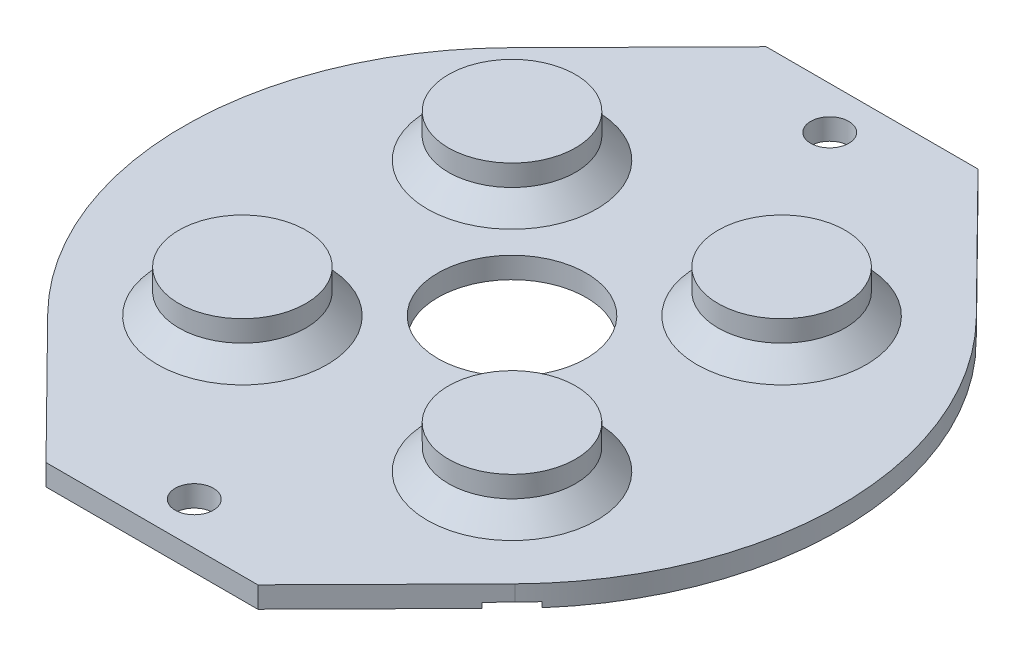
SolidWorks part; units mm, degrees
material "Silicon"
ref_plane "Front Plane" through (0, 0, 0) normal (0, 0, 1) x (1, 0, 0)
ref_plane "Top Plane" through (0, 0, 0) normal (0, 1, 0) x (1, 0, 0)
ref_plane "Right Plane" through (0, 0, 0) normal (1, 0, 0) x (0, 0, -1)
sketch "Sketch1" plane through (0, 0, 0) normal (0, 1, 0) x (1, 0, 0)
  line L0 (5, 17) -> (11.0323, 10.8876)
  line L1 (-5, -17) -> (5, -17)
  line L3 (-5, 17) -> (5, 17)
  line L7 (-5, 17) -> (-11.0323, 10.8876)
  line L8 (5, -17) -> (11.0323, -10.8876)
  line L9 (-5, -17) -> (-11.0323, -10.8876)
  arc A0 (-11.0323, 10.8876) -> (-11.0323, -10.8876) centre (0, 0) ccw
  arc A1 (11.0323, -10.8876) -> (11.0323, 10.8876) centre (0, 0) ccw
  point P0 (0, 0)
  dimension "D1" = 34
  dimension "D3" = 31
  dimension "D2" = 10
extrude "Boss-Extrude1" add sketch "Sketch1" along normal blind 1
sketch "Sketch2" plane through (0, 1, 0) normal (0, 1, 0) x (1, 0, 0)
  circle A0 centre (0, 0) radius 3.5
  dimension "D1" = 7
extrude "Cut-Extrude1" cut sketch "Sketch2" against normal through all
sketch "Sketch3" plane through (0, 1, 0) normal (0, 1, 0) x (1, 0, 0)
  line L0 (-20.9402, 0) -> (18.8298, 0) construction
  line L1 (-6.364, 6.364) -> (0, 0) construction
  circle A0 centre (0, 0) radius 9 construction
  circle A1 centre (-6.364, 6.364) radius 3
  dimension "D3" = 45
  dimension "D1" = 18
  dimension "D2" = 6
extrude "Boss-Extrude2" add sketch "Sketch3" along normal blind 2
pattern_circular "CirPattern1" count 4 over 360 about axis through (0, 0, 0) along (0, 1, 0) of "Boss-Extrude2"
chamfer "Chamfer1" distance 1 angle 45 4 edges at (-3.364, 1, 6.364) (6.364, 1, 3.364) (3.364, 1, -6.364) (-6.364, 1, -3.364)
ref_plane "Plane1" through (0, 0, 0) normal (0.7071, 0, -0.7071) x (-0.7071, 0, -0.7071)
sketch "Sketch4" plane through (0, 0, 0) normal (0.7071, 0, -0.7071) x (-0.7071, 0, -0.7071)
  line L0 (9, 1) -> (9, 4.3226) construction
  line L3 (12.5, 0) -> (9, 0)
  line L4 (8.4853, 0) -> (15.5563, 0) construction
  line L5 (9, 0) -> (9, 1.75)
  line L6 (9, 1.75) -> (11.5, 1.75)
  line L7 (11.5, 1.75) -> (12.5, 0.5)
  line L8 (12.5, 0.5) -> (12.5, 0)
  dimension "D2" = 3.5
  dimension "D3" = 0.5
  dimension "D4" = 2.5
  dimension "D5" = 1.75
  dimension "D1" = 9
revolve "Cut-Revolve1" cut sketch "Sketch4" angle 360 about L0
pattern_circular "CirPattern2" count 4 over 360 about axis through (0, 0, 0) along (0, 1, 0) of "Cut-Revolve1"
sketch "Sketch5" plane through (0, 0, 0) normal (0, -1, 0) x (1, 0, 0)
  line L0 (-3.0099, 7.364) -> (3.0099, 7.364)
  line L1 (-7.364, 3.0099) -> (-7.364, -3.0099)
  line L2 (-3.0099, 5.364) -> (3.0099, 5.364)
  line L3 (-5.364, 3.0099) -> (-5.364, -3.0099)
  line L4 (-3.0099, -5.364) -> (3.0099, -5.364)
  line L5 (-3.0099, -7.364) -> (3.0099, -7.364)
  line L6 (5.364, -3.0099) -> (5.364, 3.0099)
  line L7 (7.364, -3.0099) -> (7.364, 3.0099)
  line L8 (8.0286, 9.4428) -> (10.258, 11.6722)
  line L9 (5, 17) -> (11.0323, 10.8876) construction
  line L10 (9.4428, 8.0286) -> (11.6444, 10.2302)
  line L11 (-8.0286, 9.4428) -> (-10.258, 11.6722)
  line L12 (-11.0323, 10.8876) -> (-5, 17) construction
  line L13 (-9.4428, 8.0286) -> (-11.6444, 10.2302)
  line L14 (-8.0286, -9.4428) -> (-10.258, -11.6722)
  line L15 (-5, -17) -> (-11.0323, -10.8876) construction
  line L16 (-9.4428, -8.0286) -> (-11.6444, -10.2302)
  line L17 (8.0286, -9.4428) -> (10.258, -11.6722)
  line L18 (11.0323, -10.8876) -> (5, -17) construction
  line L19 (9.4428, -8.0286) -> (11.6444, -10.2302)
  line L20 (-10.258, -11.6722) -> (-11.0323, -10.8876)
  line L21 (-6.364, -6.364) -> (6.364, -6.364) construction
  line L22 (-6.364, -6.364) -> (-6.364, 6.364) construction
  line L23 (-6.364, 6.364) -> (6.364, 6.364) construction
  line L24 (6.364, -6.364) -> (6.364, 6.364) construction
  line L25 (-6.364, -6.364) -> (6.364, 6.364) construction
  line L26 (-6.364, 6.364) -> (6.364, -6.364) construction
  line L27 (11.0323, -10.8876) -> (10.258, -11.6722)
  line L28 (10.258, 11.6722) -> (11.0323, 10.8876)
  line L29 (-11.0323, 10.8876) -> (-10.258, 11.6722)
  circle A0 centre (-6.364, 6.364) radius 3.5 construction
  circle A1 centre (6.364, 6.364) radius 3.5 construction
  circle A2 centre (-6.364, 6.364) radius 3.5 construction
  circle A3 centre (6.364, 6.364) radius 3.5 construction
  circle A4 centre (-6.364, -6.364) radius 3.5 construction
  circle A5 centre (-6.364, -6.364) radius 3.5 construction
  circle A6 centre (6.364, -6.364) radius 3.5 construction
  circle A7 centre (6.364, -6.364) radius 3.5 construction
  arc A8 (11.0323, -10.8876) -> (11.0323, 10.8876) centre (0, 0) ccw construction
  arc A9 (-11.0323, 10.8876) -> (-11.0323, -10.8876) centre (0, 0) ccw construction
  arc A10 (-3.0099, -7.364) -> (-3.0099, -5.364) centre (-6.364, -6.364) ccw
  arc A11 (3.0099, -5.364) -> (3.0099, -7.364) centre (6.364, -6.364) ccw
  arc A12 (3.0099, 7.364) -> (3.0099, 5.364) centre (6.364, 6.364) ccw
  arc A13 (-8.0286, 9.4428) -> (-9.4428, 8.0286) centre (-6.364, 6.364) ccw
  arc A14 (-7.364, 3.0099) -> (-5.364, 3.0099) centre (-6.364, 6.364) ccw
  arc A15 (-3.0099, 5.364) -> (-3.0099, 7.364) centre (-6.364, 6.364) ccw
  arc A16 (9.4428, 8.0286) -> (8.0286, 9.4428) centre (6.364, 6.364) ccw
  arc A17 (5.364, 3.0099) -> (7.364, 3.0099) centre (6.364, 6.364) ccw
  arc A18 (7.364, -3.0099) -> (5.364, -3.0099) centre (6.364, -6.364) ccw
  arc A19 (8.0286, -9.4428) -> (9.4428, -8.0286) centre (6.364, -6.364) ccw
  arc A20 (-9.4428, -8.0286) -> (-8.0286, -9.4428) centre (-6.364, -6.364) ccw
  arc A21 (-5.364, -3.0099) -> (-7.364, -3.0099) centre (-6.364, -6.364) ccw
  arc A22 (11.0323, -10.8876) -> (11.6444, -10.2302) centre (0, 0) ccw
  arc A23 (-11.0323, 10.8876) -> (-11.6444, 10.2302) centre (0, 0) ccw
  arc A24 (-11.6444, -10.2302) -> (-11.0323, -10.8876) centre (0, 0) ccw
  arc A25 (11.6444, 10.2302) -> (11.0323, 10.8876) centre (0, 0) ccw
  point P62 (0, 0)
  dimension "D1" = 2
  dimension "D2" = 2
  dimension "D3" = 2
  dimension "D4" = 2
  dimension "D5" = 2
  dimension "D6" = 2
  dimension "D7" = 2
  dimension "D8" = 2
extrude "Cut-Extrude4" cut sketch "Sketch5" against normal blind 0.25
sketch "Sketch6" plane through (0, 1.75, 0) normal (0, -1, 0) x (1, 0, 0)
  circle A0 centre (-6.364, -6.364) radius 2.5 construction
  circle A1 centre (-6.364, -6.364) radius 2.5
extrude "Boss-Extrude3" add sketch "Sketch6" along normal blind 0.5
pattern_circular "CirPattern3" count 4 over 360 about axis through (0, 0, 0) along (0, 1, 0) of "Boss-Extrude3"
sketch "Sketch7" plane through (0, 1, 0) normal (0, 1, 0) x (1, 0, 0)
  line L0 (5, 17) -> (-5, 17) construction
  circle A0 centre (0, 15) radius 0.9
  dimension "D1" = 1.8
  dimension "D2" = 2
extrude "Cut-Extrude5" cut sketch "Sketch7" against normal through all
mirror "Mirror1" about plane through (0, 0, 0) normal (0, 0, 1) of "Cut-Extrude5"
